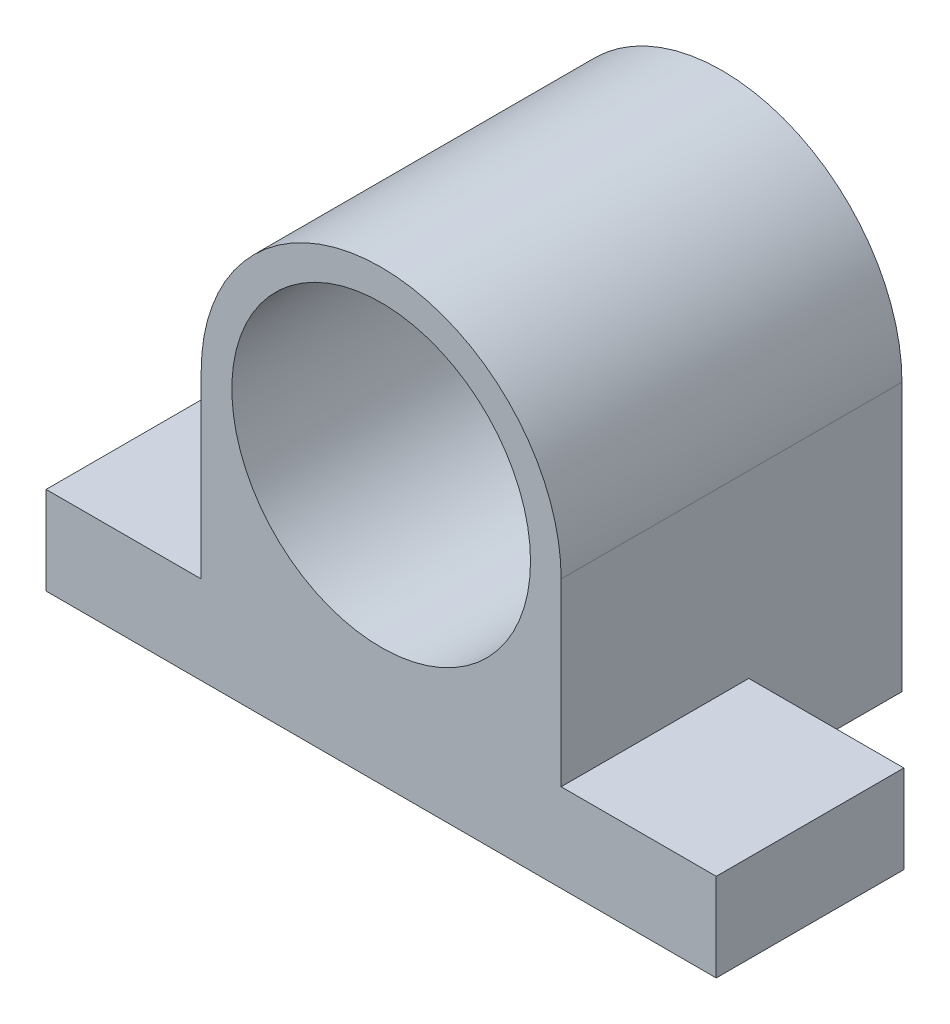
SolidWorks part; units mm, degrees
ref_plane "Front Plane" through (0, 0, 0) normal (0, 0, 1) x (1, 0, 0)
ref_plane "Top Plane" through (0, 0, 0) normal (0, 1, 0) x (1, 0, 0)
ref_plane "Right Plane" through (0, 0, 0) normal (1, 0, 0) x (0, 0, -1)
sketch "Sketch1" plane through (0, 0, 0) normal (0, 0, 1) x (1, 0, 0)
  line L0 (11.938, 0) -> (11.938, -11.938)
  line L1 (11.938, -11.938) -> (22.225, -11.938)
  line L2 (22.225, -11.938) -> (22.225, -17.78)
  line L3 (22.225, -17.78) -> (-22.225, -17.78)
  line L4 (-22.225, -17.78) -> (-22.225, -11.938)
  line L5 (-22.225, -11.938) -> (-11.938, -11.938)
  line L6 (-11.938, -11.938) -> (-11.938, 0)
  line L7 (0, 0) -> (0, -32.5713) construction
  circle A0 centre (0, 0) radius 8.763
  arc A1 (11.938, 0) -> (-11.938, 0) centre (0, 0) ccw
  dimension "D1" = 17.526
  dimension "D2" = 3.175
  dimension "D3" = 17.78
  dimension "D4" = 44.45
extrude "Boss-Extrude1" add sketch "Sketch1" along normal blind 3.556
sketch "Sketch2" plane through (0, 0, 3.556) normal (0, 0, 1) x (1, 0, 0)
  line L7 (-11.938, 0) -> (-11.938, -11.938)
  line L8 (-11.938, -11.938) -> (-22.225, -11.938)
  line L9 (-22.225, -11.938) -> (-22.225, -17.78)
  line L10 (-22.225, -17.78) -> (22.225, -17.78)
  line L11 (22.225, -17.78) -> (22.225, -11.938)
  line L12 (22.225, -11.938) -> (11.938, -11.938)
  line L13 (11.938, -11.938) -> (11.938, 0)
  line L14 (-11.938, 0) -> (-11.938, -11.938)
  line L15 (-11.938, -11.938) -> (-22.225, -11.938)
  line L16 (-22.225, -11.938) -> (-22.225, -17.78)
  line L17 (-22.225, -17.78) -> (22.225, -17.78)
  line L18 (22.225, -17.78) -> (22.225, -11.938)
  line L19 (22.225, -11.938) -> (11.938, -11.938)
  line L20 (11.938, -11.938) -> (11.938, 0)
  arc A1 (11.938, 0) -> (-11.938, 0) centre (0, 0) ccw
  arc A2 (11.938, 0) -> (-11.938, 0) centre (0, 0) ccw
  dimension "D1" = 0
extrude "Boss-Extrude2" add sketch "Sketch2" along normal blind 19.05
sketch "Sketch3" plane through (0, 0, 22.606) normal (0, 0, 1) x (1, 0, 0)
  circle A0 centre (0, 0) radius 9.906
  dimension "D1" = 19.812
extrude "Cut-Extrude1" cut sketch "Sketch3" against normal blind 17.78
sketch "Sketch4" plane through (0, 0, 4.826) normal (0, 0, 1) x (1, 0, 0)
  circle A0 centre (0, 0) radius 6.35
  dimension "D1" = 12.7
extrude "Cut-Extrude2" cut sketch "Sketch4" against normal blind 17.78
sketch "Sketch5" plane through (0, -11.938, 0) normal (0, 1, 0) x (1, 0, 0)
  line L0 (11.938, -22.606) -> (11.938, 0) construction
  line L1 (11.938, -10.16) -> (22.225, -10.16)
  line L2 (11.938, -10.16) -> (11.938, 0)
  line L3 (11.938, 0) -> (22.225, 0)
  line L4 (22.225, -10.16) -> (22.225, 0)
  line L5 (-22.225, -22.606) -> (-22.225, 0) construction
  line L6 (-22.225, -10.16) -> (-11.938, -10.16)
  line L7 (-22.225, -10.16) -> (-22.225, 0)
  line L8 (-22.225, 0) -> (-11.938, 0)
  line L9 (-11.938, -10.16) -> (-11.938, 0)
  dimension "D1" = 10.16
  dimension "D2" = 10.16
extrude "Cut-Extrude3" cut sketch "Sketch5" against normal blind 12.7
